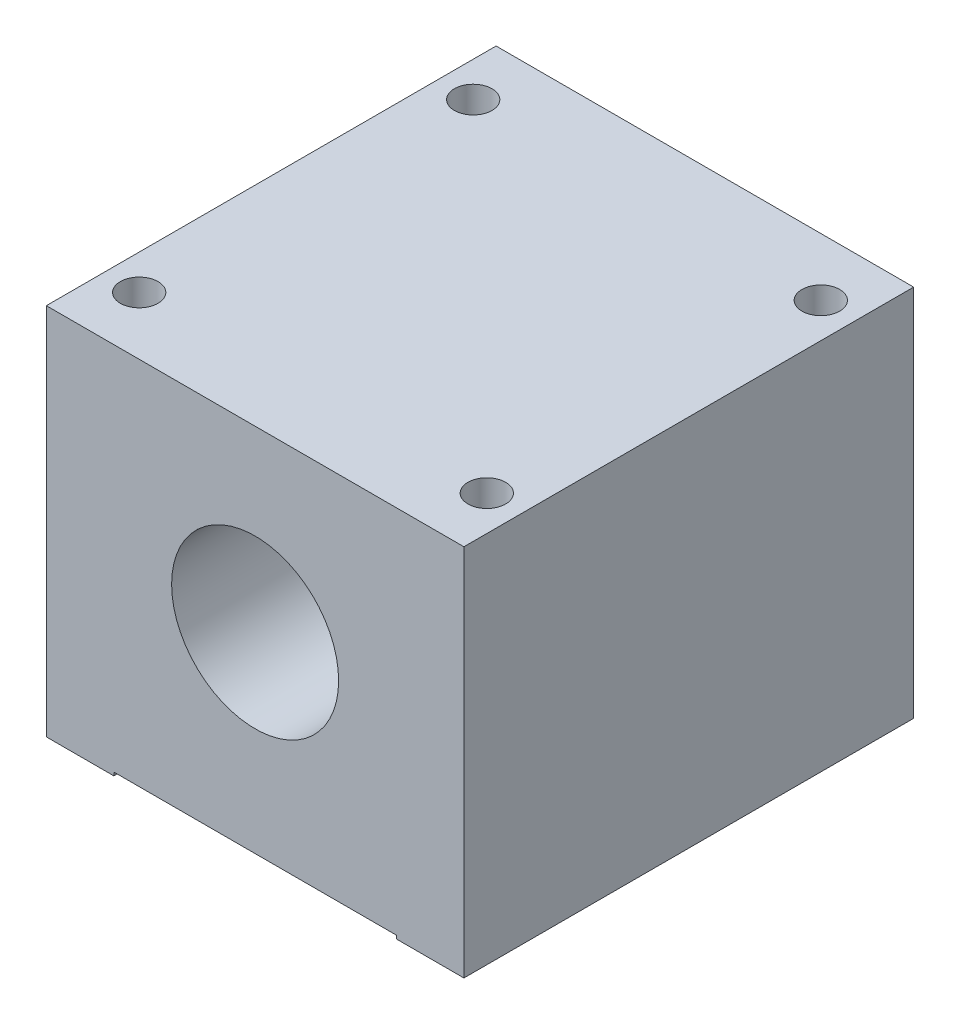
SolidWorks part; units mm, degrees
ref_plane "Front Plane" through (0, 0, 0) normal (0, 0, 1) x (1, 0, 0)
ref_plane "Top Plane" through (0, 0, 0) normal (0, 1, 0) x (1, 0, 0)
ref_plane "Right Plane" through (0, 0, 0) normal (1, 0, 0) x (0, 0, -1)
sketch "Sketch1" plane through (0, 0, 0) normal (0, 1, 0) x (1, 0, 0)
  line L1 (-70.5375, 37.9174) -> (-22.9075, 37.9174)
  line L2 (-70.5375, 37.9174) -> (-70.5375, -13.3826)
  line L3 (-70.5375, -13.3826) -> (-22.9075, -13.3826)
  line L4 (-22.9075, 37.9174) -> (-22.9075, -13.3826)
  line L5 (-70.5375, 37.9174) -> (-22.9075, -13.3826) construction
  line L6 (-70.5375, -13.3826) -> (-22.9075, 37.9174) construction
  circle A0 centre (-66.5475, 31.3174) radius 2.15
  circle A1 centre (-26.8975, 31.3174) radius 2.15
  circle A2 centre (-66.5475, -6.7826) radius 2.15
  circle A3 centre (-26.8975, -6.7826) radius 2.15
  point P0 (-46.7225, 12.2674)
  dimension "D3" = 6.6
  dimension "D4" = 3.99
  dimension "D6" = 3.99
  dimension "D8" = 4.3
  dimension "D9" = 4.3
  dimension "D11" = 4.3
  dimension "D1" = 51.3
  dimension "D2" = 47.63
  dimension "D5" = 3.99
  dimension "D7" = 6.6
extrude "Boss-Extrude1" add sketch "Sketch1" along normal blind 42.6
sketch "Sketch2" plane through (0, 0, 13.3826) normal (0, 0, 1) x (1, 0, 0)
  line L0 (-70.5375, 0) -> (-22.9075, 0) construction
  circle A0 centre (-46.7225, 22.23) radius 9.525
  dimension "D1" = 22.23
extrude "Cut-Extrude1" cut sketch "Sketch2" against normal through all
sketch "Sketch3" plane through (0, 0, 0) normal (0, -1, 0) x (1, 0, 0)
  line L0 (-70.5375, -37.9174) -> (-70.5375, 13.3826) construction
  line L1 (-62.8375, 17.1604) -> (-30.6075, 17.1604)
  line L2 (-62.8375, 17.1604) -> (-62.8375, -39.8882)
  line L3 (-62.8375, -39.8882) -> (-30.6075, -39.8882)
  line L4 (-30.6075, 17.1604) -> (-30.6075, -39.8882)
  line L5 (-62.8375, 17.1604) -> (-30.6075, -39.8882) construction
  line L6 (-62.8375, -39.8882) -> (-30.6075, 17.1604) construction
  point P0 (-46.7225, -11.3639)
  dimension "D1" = 7.7
  dimension "D2" = 39.93
extrude "Cut-Extrude2" cut sketch "Sketch3" against normal blind 0.38
